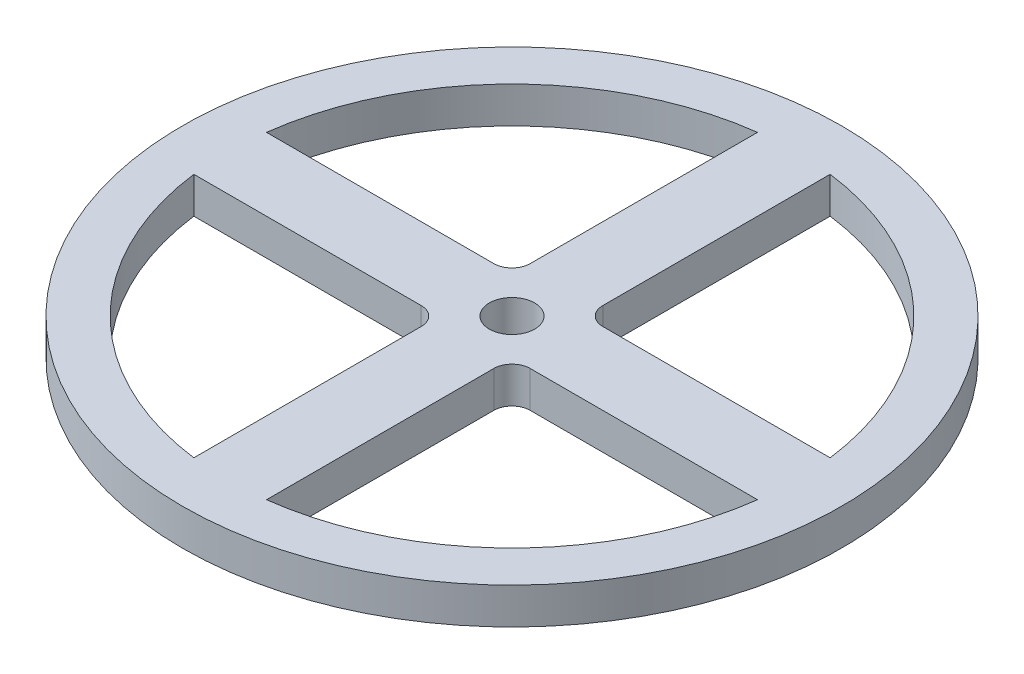
SolidWorks part; units mm, degrees
ref_plane "Front Plane" through (0, 0, 0) normal (0, 0, 1) x (1, 0, 0)
ref_plane "Top Plane" through (0, 0, 0) normal (0, 1, 0) x (1, 0, 0)
ref_plane "Right Plane" through (0, 0, 0) normal (1, 0, 0) x (0, 0, -1)
sketch "Sketch1" plane through (0, 0, 0) normal (0, 1, 0) x (1, 0, 0)
  line L0 (-43.2051, 0) -> (60.4147, 0) construction
  line L1 (0, 48.3176) -> (0, -50.4298) construction
  line L2 (-31.0434, -4) -> (-6, -4)
  line L3 (-4, 31.0434) -> (-4, 6)
  line L4 (-31.0434, 4) -> (-6, 4)
  line L5 (4, 31.0434) -> (4, 6)
  line L6 (-4, -6) -> (-4, -31.0434)
  line L7 (-4, 48.3176) -> (-4, -50.4298) construction
  line L8 (4, 48.3176) -> (4, -50.4298) construction
  line L9 (-43.2051, 4) -> (60.4147, 4) construction
  line L10 (-43.2051, -4) -> (60.4147, -4) construction
  line L11 (6, 4) -> (31.0434, 4)
  line L12 (6, -4) -> (31.0434, -4)
  line L13 (4, -6) -> (4, -31.0434)
  circle A0 centre (0, 0) radius 36.3
  circle A1 centre (0, 0) radius 2.5
  arc A2 (-31.0434, -4) -> (-4, -31.0434) centre (0, 0) ccw
  arc A5 (-6, -4) -> (-4, -6) centre (-6, -6) cw
  arc A6 (-6, 4) -> (-4, 6) centre (-6, 6) ccw
  arc A7 (4, 6) -> (6, 4) centre (6, 6) ccw
  arc A9 (6, -4) -> (4, -6) centre (6, -6) ccw
  arc A10 (-4, 31.0434) -> (-31.0434, 4) centre (0, 0) ccw
  circle A11 centre (0, 0) radius 31.3 construction
  arc A12 (31.0434, 4) -> (4, 31.0434) centre (0, 0) ccw
  arc A13 (4, -31.0434) -> (31.0434, -4) centre (0, 0) ccw
  point P38 (29.9323, 9.1512)
  dimension "D1" = 72.6
  dimension "D2" = 5
  dimension "D4" = 2
  dimension "D7" = 2
  dimension "D8" = 2
  dimension "D9" = 2
  dimension "D3" = 5
  dimension "D5" = 4
  dimension "D6" = 4
extrude "Boss-Extrude1" add sketch "Sketch1" along normal blind 4 contours A0 A13 L13 A9 L12 A12 L11 A7 L5 A10 L3 A6 L4 A1 L2 A5 L6 A2
